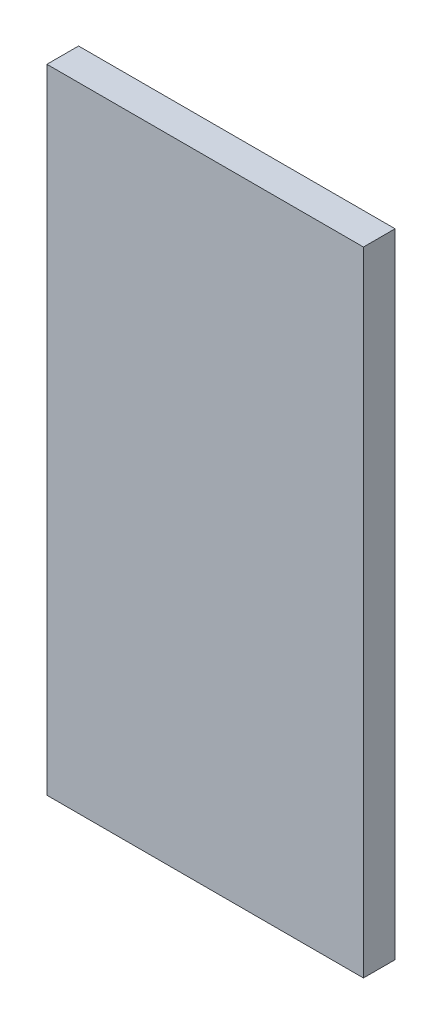
SolidWorks part; units mm, degrees
ref_plane "Front Plane" through (0, 0, 0) normal (0, 0, 1) x (1, 0, 0)
ref_plane "Top Plane" through (0, 0, 0) normal (0, 1, 0) x (1, 0, 0)
ref_plane "Right Plane" through (0, 0, 0) normal (1, 0, 0) x (0, 0, -1)
sketch "Sketch1" plane through (0, 0, 0) normal (0, 0, 1) x (1, 0, 0)
  line L1 (-53.967, 958.6136) -> (446.033, 958.6136)
  line L2 (-53.967, 958.6136) -> (-53.967, -41.3864)
  line L3 (-53.967, -41.3864) -> (446.033, -41.3864)
  line L4 (446.033, 958.6136) -> (446.033, -41.3864)
extrude "Boss-Extrude1" add sketch "Sketch1" along normal blind 50 contours L4 L3 L2 L1
